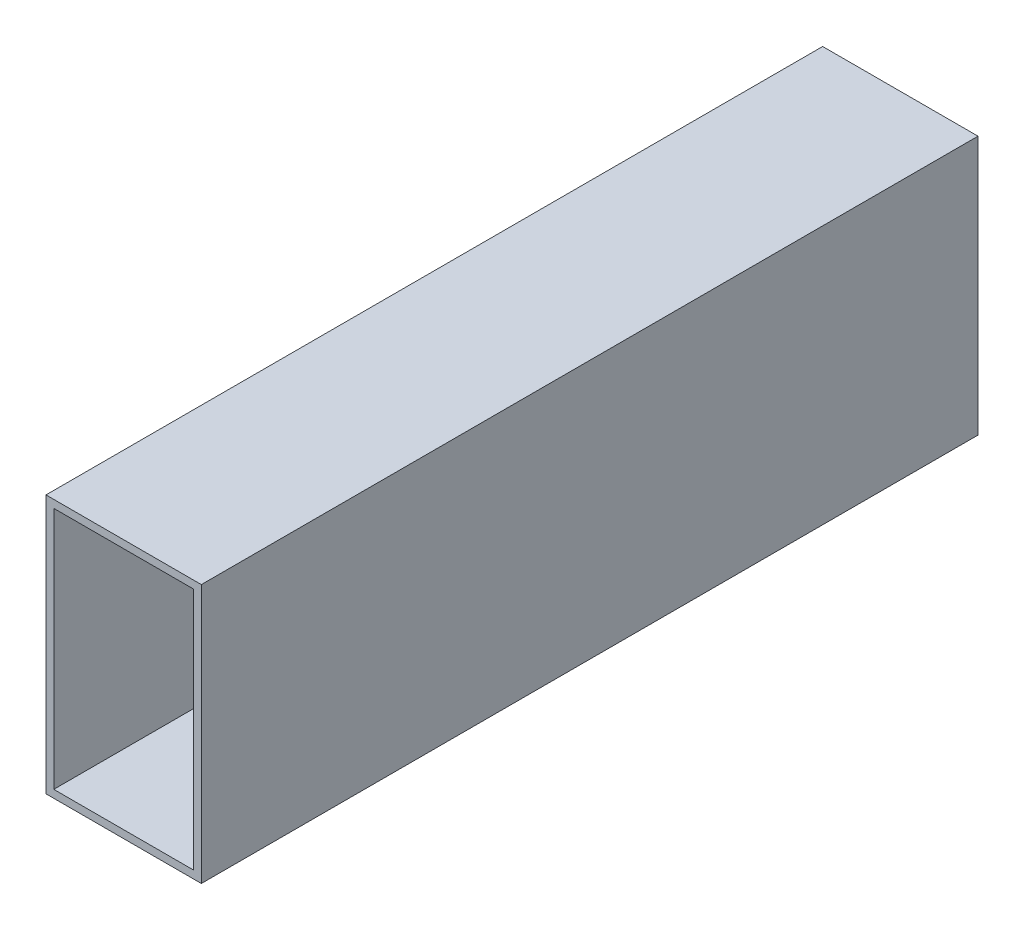
SolidWorks part; units mm, degrees
ref_plane "Plano frontal" through (0, 0, 0) normal (0, 0, 1) x (1, 0, 0)
ref_plane "Plano superior" through (0, 0, 0) normal (0, 1, 0) x (1, 0, 0)
ref_plane "Plano direito" through (0, 0, 0) normal (1, 0, 0) x (0, 0, -1)
sketch "Esboço1" plane through (0, 0, 0) normal (0, 0, 1) x (1, 0, 0)
  line L1 (0, 0) -> (30, 0)
  line L2 (0, 0) -> (0, 50)
  line L3 (0, 50) -> (30, 50)
  line L4 (30, 0) -> (30, 50)
  line L5 (1.5, 1.5) -> (28.5, 1.5)
  line L6 (1.5, 1.5) -> (1.5, 48.5)
  line L7 (1.5, 48.5) -> (28.5, 48.5)
  line L8 (28.5, 1.5) -> (28.5, 48.5)
  dimension "D1" = 50
  dimension "D2" = 30
  dimension "D3" = 1.5
  dimension "D4" = 1.5
  dimension "D5" = 1.5
  dimension "D6" = 1.5
extrude "Ressalto-extrusão1" add sketch "Esboço1" along normal blind 150
